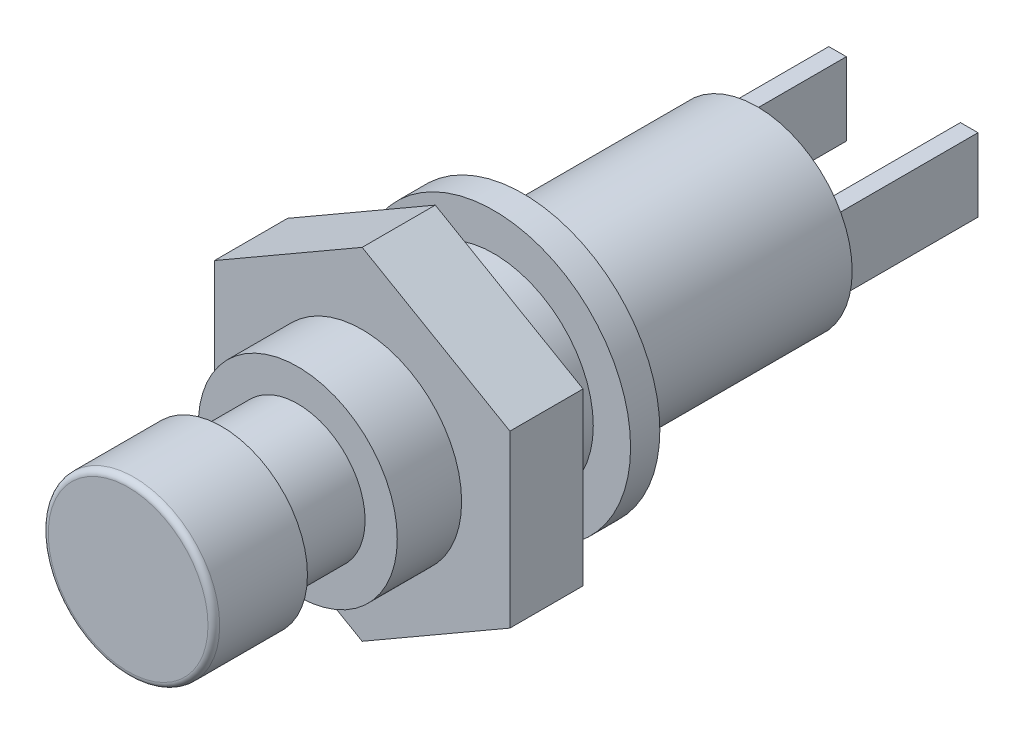
SolidWorks part; units mm, degrees
ref_plane "Front" through (0, 0, 0) normal (0, 0, 1) x (1, 0, 0)
ref_plane "Top" through (0, 0, 0) normal (0, 1, 0) x (1, 0, 0)
ref_plane "Right" through (0, 0, 0) normal (1, 0, 0) x (0, 0, -1)
sketch "Sketch1" plane through (0, 0, 0) normal (0, 0, 1) x (1, 0, 0)
  circle A0 centre (0, 0) radius 4.675
  dimension "D1" = 9.35
extrude "Collar" add sketch "Sketch1" against normal blind 1
sketch "Sketch2" plane through (0, 0, 0) normal (0, 0, 1) x (1, 0, 0)
  circle A0 centre (0, 0) radius 3.4
  dimension "D1" = 6.8
extrude "Front Body" add sketch "Sketch2" along normal blind 6.7
sketch "Sketch4" plane through (0, 0, 6.7) normal (0, 0, 1) x (1, 0, 0)
  circle A0 centre (0, 0) radius 2.3
  dimension "D1" = 4.6
extrude "Shaft" add sketch "Sketch4" along normal blind 2.6
sketch "Sketch5" plane through (0, 0, 9.3) normal (0, 0, 1) x (1, 0, 0)
  circle A0 centre (0, 0) radius 2.93
  dimension "D1" = 5.86
extrude "Knob" add sketch "Sketch5" along normal blind 3.2
fillet "Knob Fillet" radius 0.2 1 edges at (2.93, 0, 12.5)
sketch "Sketch3" plane through (0, 0, 0) normal (0, 0, 1) x (1, 0, 0)
  circle A0 centre (0, 0) radius 3.25
  dimension "D1" = 6.5
extrude "Rear Body" add sketch "Sketch3" against normal blind 9
sketch "Sketch6" plane through (0, 0, -9) normal (0, 0, -1) x (-1, 0, 0)
  line L0 (-2.25, 0) -> (0, 0) construction
  line L1 (-1.95, 1.25) -> (-2.55, 1.25)
  line L2 (-1.95, 1.25) -> (-1.95, -1.25)
  line L3 (-1.95, -1.25) -> (-2.55, -1.25)
  line L4 (-2.55, 1.25) -> (-2.55, -1.25)
  line L5 (-1.95, 1.25) -> (-2.55, -1.25) construction
  line L6 (-1.95, -1.25) -> (-2.55, 1.25) construction
  line L7 (1.95, -1.25) -> (2.55, -1.25)
  line L8 (1.95, -1.25) -> (1.95, 1.25)
  line L9 (1.95, 1.25) -> (2.55, 1.25)
  line L10 (2.55, -1.25) -> (2.55, 1.25)
  line L11 (1.95, -1.25) -> (2.55, 1.25) construction
  line L12 (1.95, 1.25) -> (2.55, -1.25) construction
  line L13 (0, 0) -> (2.25, 0) construction
  point P0 (-2.25, 0)
  point P5 (2.25, 0)
  dimension "D1" = 4.5
  dimension "D2" = 2.5
  dimension "D3" = 0.6
extrude "Pins" add sketch "Sketch6" along normal blind 5
ref_plane "Nut Plane" through (0, 0, 2) normal (0, 0, 1) x (1, 0, 0)
sketch "Sketch7" plane through (0, 0, 2) normal (0, 0, 1) x (1, 0, 0)
  line L1 (0, 5.8312) -> (-5.05, 2.9156)
  line L2 (-5.05, 2.9156) -> (-5.05, -2.9156)
  line L3 (-5.05, -2.9156) -> (0, -5.8312)
  line L4 (0, -5.8312) -> (5.05, -2.9156)
  line L5 (5.05, -2.9156) -> (5.05, 2.9156)
  line L6 (5.05, 2.9156) -> (0, 5.8312)
  circle A0 centre (0, 0) radius 5.05 construction
  dimension "D1" = 10.1
extrude "Nut" add sketch "Sketch7" along normal blind 2.5
sketch "Panel Cut Mount" plane through (0, 0, 0) normal (0, 0, 1) x (1, 0, 0)
  circle A0 centre (0, 0) radius 3.45
  dimension "D1" = 6.9
